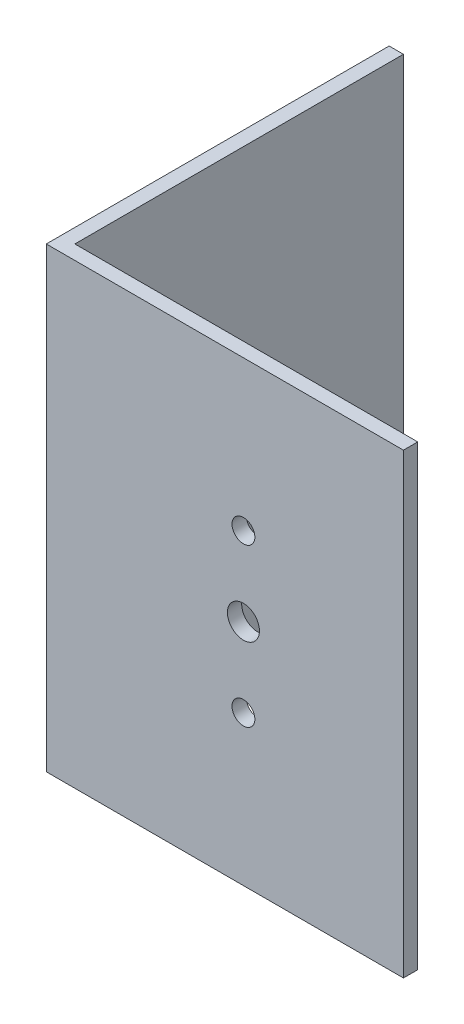
SolidWorks part; units mm, degrees
material "6061-T6 (SS)"
ref_plane "X-Y Datum" through (0, 0, 0) normal (0, 0, 1) x (1, 0, 0)
ref_plane "X-Z Datum" through (0, 0, 0) normal (0, 1, 0) x (1, 0, 0)
ref_plane "Y-Z Datum" through (0, 0, 0) normal (1, 0, 0) x (0, 0, -1)
sketch "Sketch2" plane through (0, 0, 0) normal (1, 0, 0) x (0, 0, -1)
  line L1 (19.05, -25.4) -> (-19.05, -25.4)
  line L2 (19.05, -25.4) -> (19.05, 25.4)
  line L3 (19.05, 25.4) -> (-19.05, 25.4)
  line L4 (-19.05, -25.4) -> (-19.05, 25.4)
  line L5 (19.05, -25.4) -> (-19.05, 25.4) construction
  line L6 (19.05, 25.4) -> (-19.05, -25.4) construction
  point P0 (0, 0)
  dimension "D1" = 50.8
  dimension "D2" = 38.1
extrude "Boss-Extrude1" add sketch "Sketch2" along normal blind 1.5875
sketch "Sketch3" plane through (1.5875, 0, 0) normal (1, 0, 0) x (0, 0, -1)
  line L0 (19.05, 25.4) -> (-19.05, 25.4) construction
  line L1 (-19.05, -25.4) -> (-17.4625, -25.4)
  line L2 (-19.05, -25.4) -> (-19.05, 25.4)
  line L3 (-19.05, 25.4) -> (-17.4625, 25.4)
  line L4 (-17.4625, -25.4) -> (-17.4625, 25.4)
  dimension "D1" = 1.5875
extrude "Boss-Extrude2" add sketch "Sketch3" along normal blind 38.1
sketch "Sketch4" plane through (0, 0, 19.05) normal (0, 0, 1) x (1, 0, 0)
  line L0 (39.6875, 25.4) -> (39.6875, -25.4) construction
  line L1 (55, 0) -> (-55, 0) construction
  circle A0 centre (21.9075, 0) radius 1.778
  circle A1 centre (21.9075, 8.763) radius 1.27
  circle A2 centre (21.9075, -8.763) radius 1.27
  dimension "D1" = 2.54
  dimension "D2" = 3.556
  dimension "D3" = 8.763
  dimension "D4" = 17.78
  dimension "D5" = 8.763
extrude "Cut-Extrude1" cut sketch "Sketch4" against normal up to next
